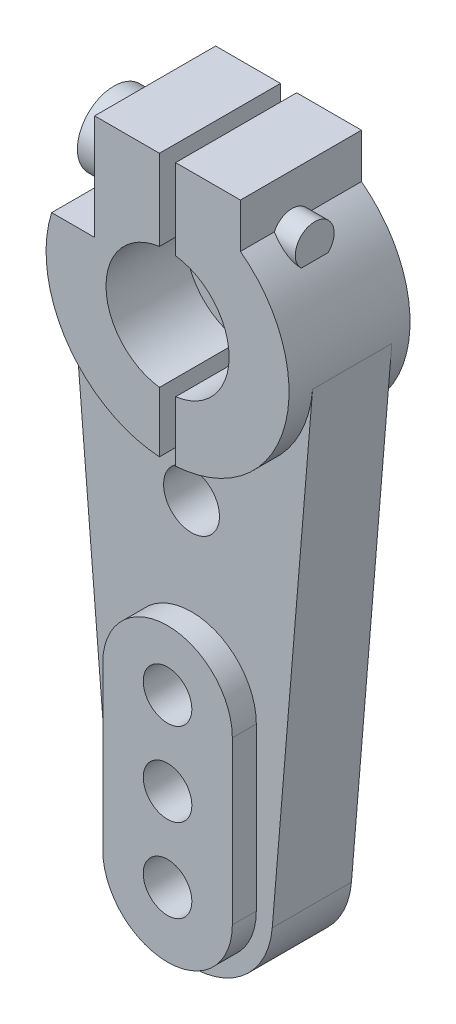
SolidWorks part; units mm, degrees
ref_plane "Alzado" through (0, 0, 0) normal (0, 0, 1) x (1, 0, 0)
ref_plane "Planta" through (0, 0, 0) normal (0, 1, 0) x (1, 0, 0)
ref_plane "Vista lateral" through (0, 0, 0) normal (1, 0, 0) x (0, 0, -1)
sketch "Croquis1" plane through (0, 0, 0) normal (0, 0, 1) x (1, 0, 0)
  line L0 (0, 0) -> (4.5, 0) construction
  line L1 (0, 0) -> (-4.5, 0) construction
  line L2 (4.5, 6) -> (4.5, 8.75)
  line L3 (-4.5, 6) -> (-4.5, 8.75)
  line L4 (-4.5, 8.75) -> (4.5, 8.75)
  line L5 (0, 8.75) -> (0, 0) construction
  line L6 (0, -35.25) -> (0, -30.25) construction
  line L7 (4.9829, -30.6632) -> (7.4743, -0.6198)
  line L8 (-4.9829, -30.6632) -> (-7.4743, -0.6198)
  line L9 (0, -7.5) -> (0, -25.257) construction
  line L10 (0, -30.25) -> (0, -35.25) construction
  arc A0 (-4.5, 6) -> (-7.4743, -0.6198) centre (0, 0) ccw
  arc A1 (-4.9829, -30.6632) -> (4.9829, -30.6632) centre (0, -30.25) ccw
  arc A2 (7.4743, -0.6198) -> (4.5, 6) centre (0, 0) ccw
  dimension "D1" = 15
  dimension "D2" = 4.5
  dimension "D3" = 4.5
  dimension "D4" = 8.75
  dimension "D5" = 8.75
  dimension "D6" = 44
  dimension "D7" = 5
  dimension "D8" = 9
extrude "Saliente-Extruir1" add sketch "Croquis1" along normal blind 7.47
sketch "Croquis2" plane through (0, 0, 7.47) normal (0, 0, 1) x (1, 0, 0)
  line L0 (0, -30.25) -> (0, -20.25) construction
  line L1 (-4, -30.25) -> (-4, -20.25)
  line L2 (4, -30.25) -> (4, -20.25)
  line L5 (-7.4743, -0.6198) -> (-4.9829, -30.6632)
  line L6 (4.9829, -30.6632) -> (7.4743, -0.6198)
  line L7 (4.5, 6) -> (4.5, 8.75)
  line L8 (4.5, 8.75) -> (-4.5, 8.75)
  line L9 (-4.5, 8.75) -> (-4.5, 6)
  line L10 (-7.4743, -0.6198) -> (-4.9829, -30.6632)
  line L11 (4.9829, -30.6632) -> (7.4743, -0.6198)
  arc A1 (-4, -30.25) -> (4, -30.25) centre (0, -30.25) ccw
  arc A2 (4, -20.25) -> (-4, -20.25) centre (0, -20.25) ccw
  arc A3 (-7.4743, -0.6198) -> (7.4743, -0.6198) centre (0, 0) ccw
  arc A4 (-4.5, 6) -> (-7.4743, -0.6198) centre (0, 0) ccw
  arc A5 (-4.9829, -30.6632) -> (4.9829, -30.6632) centre (0, -30.25) ccw
  arc A6 (7.4743, -0.6198) -> (4.5, 6) centre (0, 0) ccw
  arc A8 (-4.9829, -30.6632) -> (4.9829, -30.6632) centre (0, -30.25) ccw
  point P3 (0, -25.25)
  point P20 (0, -34.25)
  point P21 (0, -16.25)
  dimension "D3" = 8
  dimension "D4" = 18
  dimension "D1" = 0
extrude "Cortar-Extruir1" cut sketch "Croquis2" against normal blind 1.48
sketch "Croquis3" plane through (0, 0, 0) normal (0, 0, -1) x (-1, 0, 0)
  line L5 (4.5, 6) -> (4.5, 8.75)
  line L6 (4.5, 8.75) -> (-4.5, 8.75)
  line L7 (-4.5, 8.75) -> (-4.5, 6)
  line L8 (-7.4743, -0.6198) -> (-4.9829, -30.6632)
  line L9 (4.9829, -30.6632) -> (7.4743, -0.6198)
  line L13 (-7.4743, -0.6198) -> (-4.9829, -30.6632)
  line L14 (4.9829, -30.6632) -> (7.4743, -0.6198)
  arc A0 (-7.4743, -0.6198) -> (7.4743, -0.6198) centre (0, 0) ccw
  arc A3 (7.4743, -0.6198) -> (4.5, 6) centre (0, 0) ccw
  arc A4 (-4.5, 6) -> (-7.4743, -0.6198) centre (0, 0) ccw
  arc A5 (-4.9829, -30.6632) -> (4.9829, -30.6632) centre (0, -30.25) ccw
  arc A8 (-4.9829, -30.6632) -> (4.9829, -30.6632) centre (0, -30.25) ccw
  dimension "D1" = 0
extrude "Cortar-Extruir2" cut sketch "Croquis3" against normal blind 1.1
sketch "Croquis4" plane through (0, 0, 7.47) normal (0, 0, 1) x (1, 0, 0)
  line L3 (0, -19.9708) -> (0, 0) construction
  circle A7 centre (0, -19.9708) radius 1.5
  circle A11 centre (0, -25.1104) radius 1.5
  circle A12 centre (0, -30.25) radius 1.5
  dimension "D2" = 5.1396
  dimension "D1" = 3
  dimension "D3" = 19.9708
  dimension "D4" = 5.1396
extrude "Cortar-Extruir4" cut sketch "Croquis4" against normal through all
sketch "Croquis7" plane through (0, 0, 5.99) normal (0, 0, 1) x (1, 0, 0)
  line L0 (0, -10.3) -> (0, -16.25) construction
  arc A0 (4, -20.25) -> (-4, -20.25) centre (0, -20.25) ccw construction
  circle A1 centre (0, -10.3) radius 1.725
  dimension "D2" = 3.45
  dimension "D1" = 5.95
extrude "Cortar-Extruir5" cut sketch "Croquis7" against normal through all
sketch "Croquis9" plane through (0, 0, 7.47) normal (0, 0, 1) x (1, 0, 0)
  line L0 (0, -10.3) -> (0, 8.75) construction
  line L1 (4.5, 8.75) -> (-4.5, 8.75) construction
  line L2 (0.5, -10.3) -> (0.5, 8.75)
  line L3 (-0.5, -10.3) -> (-0.5, 8.75)
  line L4 (-0.5, 8.75) -> (0.5, 8.75)
  line L5 (0.5, -10.3) -> (-0.5, -10.3)
  dimension "D1" = 0.5
  dimension "D2" = 0.5
extrude "Cortar-Extruir6" cut sketch "Croquis9" against normal through all
sketch "Croquis10" plane through (0, 0, 7.47) normal (0, 0, 1) x (1, 0, 0)
  circle A0 centre (0, 0) radius 3.8
  dimension "D1" = 7.6
extrude "Cortar-Extruir7" cut sketch "Croquis10" against normal blind 4.93
sketch "Croquis11" plane through (0, 0, 2.54) normal (0, 0, 1) x (1, 0, 0)
  circle A0 centre (0, 0) radius 1.5
  dimension "D1" = 3
extrude "Cortar-Extruir8" cut sketch "Croquis11" against normal through all
sketch "Croquis12" plane through (0, 0, 0) normal (0, 0, -1) x (-1, 0, 0)
  circle A0 centre (0, 0) radius 4.45
  dimension "D1" = 8.9
extrude "Cortar-Extruir9" cut sketch "Croquis12" against normal blind 1.1
sketch "Croquis14" plane through (0, 0, 7.47) normal (0, 0, 1) x (1, 0, 0)
  line L0 (-4.5, 8.75) -> (-4.5, 2.25)
  line L1 (-4.5, 2.25) -> (-7.1545, 2.25)
  line L2 (-7.1545, 2.25) -> (-7.1545, 8.75)
  line L3 (-7.1545, 8.75) -> (-4.5, 8.75)
  arc A0 (-4.5, 6) -> (-0.5, -7.4833) centre (0, 0) ccw construction
  dimension "D1" = 6.5
extrude "Cortar-Extruir10" cut sketch "Croquis14" against normal blind 6.37
sketch "Croquis15" plane through (-4.5, 0, 0) normal (-1, 0, 0) x (0, 0, 1)
  line L0 (4.285, 2.25) -> (4.285, 8.75) construction
  line L1 (1.1, 2.25) -> (7.47, 2.25) construction
  line L2 (7.47, 8.75) -> (0, 8.75) construction
  circle A0 centre (4.285, 5.5) radius 2.25
  dimension "D1" = 4.5
extrude "Saliente-Extruir2" add sketch "Croquis15" along normal blind 2
sketch "Croquis16" plane through (4.5, 0, 0) normal (1, 0, 0) x (0, 0, -1)
  circle A0 centre (-4.285, 5.5) radius 1.2
  dimension "D1" = 2.4
extrude "Saliente-Extruir3" add sketch "Croquis16" along normal blind 1.4
